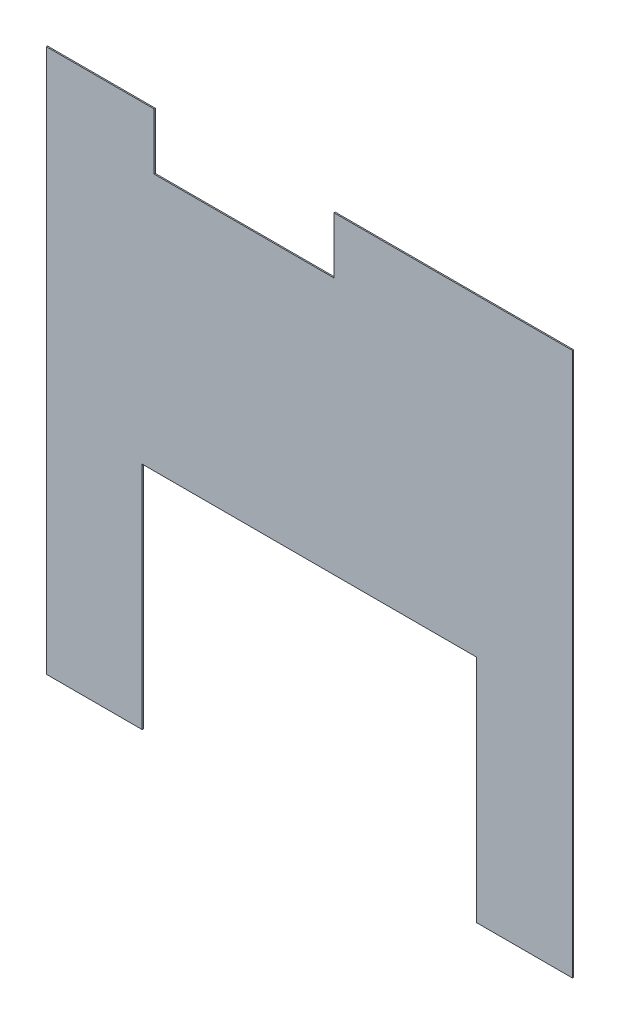
SolidWorks part; units mm, degrees
ref_plane "Alzado" through (0, 0, 0) normal (0, 0, 1) x (1, 0, 0)
ref_plane "Planta" through (0, 0, 0) normal (0, 1, 0) x (1, 0, 0)
ref_plane "Vista lateral" through (0, 0, 0) normal (1, 0, 0) x (0, 0, -1)
sketch "Croquis1" plane through (0, 0, 0) normal (0, 0, 1) x (1, 0, 0)
  line L1 (0, 0) -> (1258.2, 0)
  line L2 (0, 0) -> (0, -1300)
  line L3 (0, -1300) -> (1258.2, -1300)
  line L4 (1258.2, 0) -> (1258.2, -1300)
  dimension "D1" = 1258.2
  dimension "D2" = 1300
extrude "Saliente-Extruir1" add sketch "Croquis1" along normal blind 2.9
sketch "Croquis2" plane through (0, 0, 2.9) normal (0, 0, 1) x (1, 0, 0)
  line L0 (629.1, -1300) -> (629.1, -750) construction
  line L1 (0, -1300) -> (1258.2, -1300) construction
  line L2 (229.1, -1300) -> (229.1, -750)
  line L3 (229.1, -750) -> (1029.1, -750)
  line L4 (1029.1, -1300) -> (1029.1, -750)
  line L5 (229.1, -1300) -> (1029.1, -1300)
  dimension "D1" = 400
  dimension "D2" = 550
extrude "Cortar-Extruir1" cut sketch "Croquis2" against normal blind 2.9
sketch "Croquis3" plane through (0, 0, 2.9) normal (0, 0, 1) x (1, 0, 0)
  line L0 (1258.2, 0) -> (0, 0) construction
  line L1 (258, 0) -> (688, 0)
  line L2 (258, 0) -> (258, -135)
  line L3 (258, -135) -> (688, -135)
  line L4 (688, 0) -> (688, -135)
  line L5 (0, 0) -> (0, -1300) construction
  dimension "D1" = 430
  dimension "D2" = 258
  dimension "D3" = 135
extrude "Cortar-Extruir2" cut sketch "Croquis3" against normal blind 10
